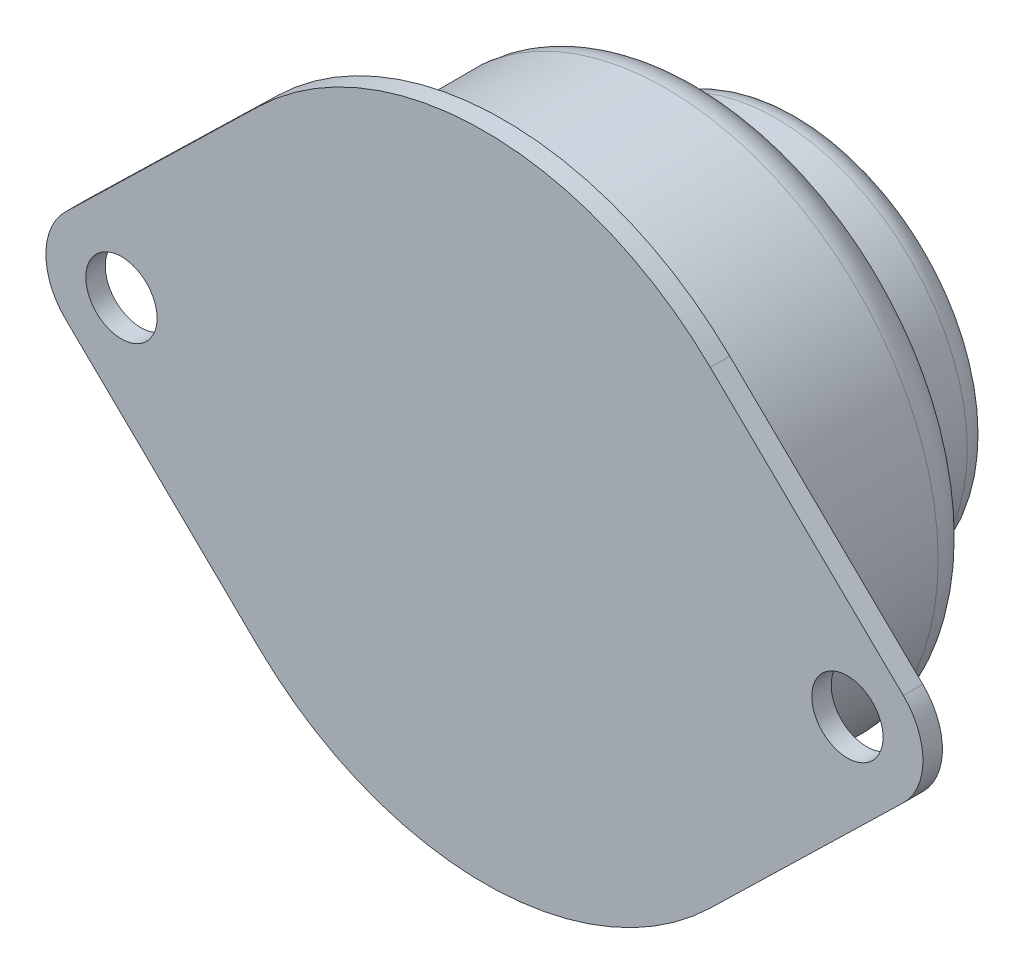
SolidWorks part; units mm, degrees
ref_plane "正面" through (0, 0, 0) normal (0, 0, 1) x (1, 0, 0)
ref_plane "平面" through (0, 0, 0) normal (0, 1, 0) x (1, 0, 0)
ref_plane "右側面" through (0, 0, 0) normal (1, 0, 0) x (0, 0, -1)
sketch "ｽｹｯﾁ2" plane through (0, 0, 0) normal (0, 0, 1) x (1, 0, 0)
  line L0 (28, 0) -> (-28, 0) construction
  line L1 (36, 0) -> (-36, 0) construction
  line L2 (0, -35) -> (0, 35) construction
  line L3 (0, -35) -> (-36, 0)
  line L4 (-36, 0) -> (0, 35)
  line L5 (0, 35) -> (36, 0)
  line L6 (36, 0) -> (0, -35)
  circle A0 centre (-28, 0) radius 2.75
  circle A1 centre (28, 0) radius 2.75
  point P4 (0, 0)
  point P10 (0, 0)
  point P13 (0, 0)
  dimension "D1" = 56
  dimension "D4" = 5.5
  dimension "D2" = 72
  dimension "D3" = 70
extrude "ﾎﾞｽ - 押し出し1" add sketch "ｽｹｯﾁ2" along normal blind 1.5
sketch "ｽｹｯﾁ3" plane through (0, 0, 1.5) normal (0, 0, 1) x (1, 0, 0)
  circle A0 centre (0, 0) radius 21
  dimension "D1" = 42
extrude "ﾎﾞｽ - 押し出し2" add sketch "ｽｹｯﾁ3" against normal blind 17
fillet "ﾌｨﾚｯﾄ4" radius 3 1 edges at (21, 0, -15.5)
sketch "ｽｹｯﾁ4" plane through (0, 0, 0) normal (0, 1, 0) x (1, 0, 0)
  line L0 (0, -1.5) -> (0, 16.8)
  line L1 (0, 29.5) -> (0, -1.5) construction
  circle A0 centre (0, 16.8) radius 12.7
  dimension "D1" = 25.4
  dimension "D2" = 31
ref_plane "平面1" through (0, 0, -16.8) normal (0, 0, -1) x (-1, 0, 0)
sketch "ｽｹｯﾁ5" plane through (0, 0, -16.8) normal (0, 0, -1) x (-1, 0, 0)
  line L0 (0, -12.7) -> (0, 12.7) construction
  line L1 (0, 12.7) -> (0, -12.7)
  arc A0 (0, 12.7) -> (0, -12.7) centre (0, 0) ccw
  point P4 (0, 0)
  dimension "D1" = 25.4
revolve "回転1" add sketch "ｽｹｯﾁ5" angle 360 about L0
sketch "ｽｹｯﾁ6" plane through (0, 0, -15.5) normal (0, 0, -1) x (-1, 0, 0)
  circle A0 centre (0, 0) radius 14.75
  dimension "D1" = 29.5
extrude "ﾎﾞｽ - 押し出し3" add sketch "ｽｹｯﾁ6" along normal blind 7.5
fillet "ﾌｨﾚｯﾄ3" radius 2 1 edges at (-14.75, 0, -23)
fillet "ﾌｨﾚｯﾄ7" radius 25 2 edges at (0, -35, 0.75) (0, 35, 0.75)
fillet "ﾌｨﾚｯﾄ8" radius 5 2 edges at (-36, 0, 0.75) (36, 0, 0.75)
